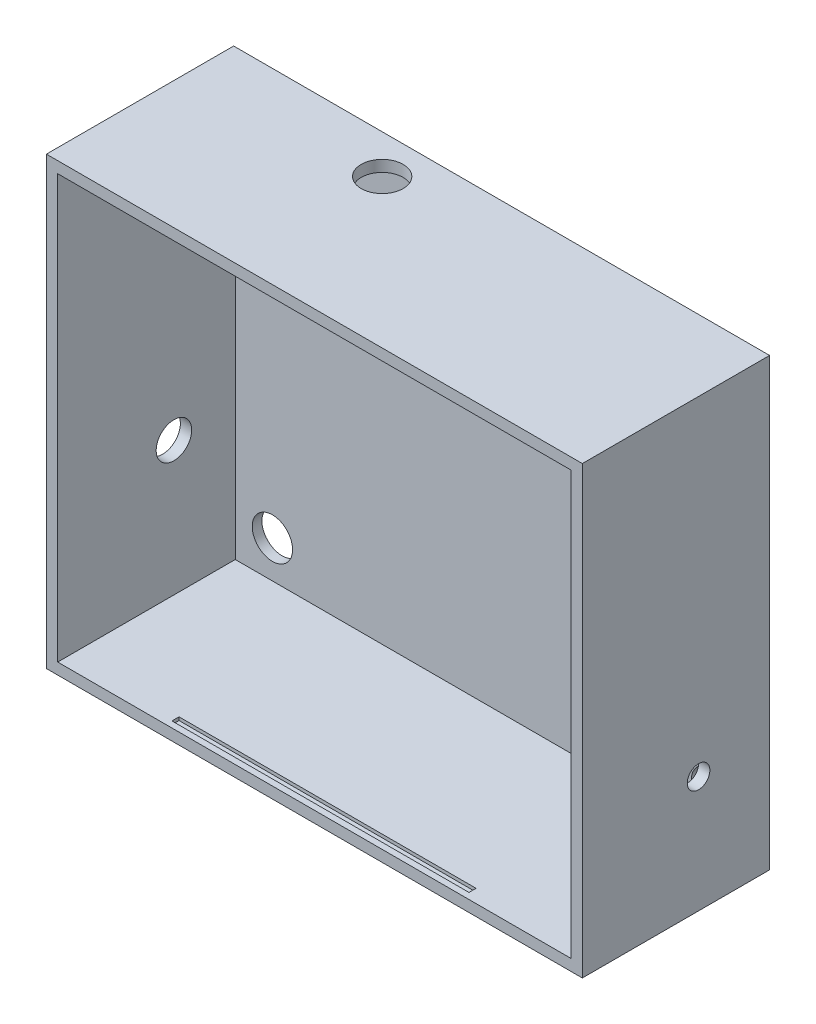
SolidWorks part; units mm, degrees
ref_plane "정면" through (0, 0, 0) normal (0, 0, 1) x (1, 0, 0)
ref_plane "윗면" through (0, 0, 0) normal (0, 1, 0) x (1, 0, 0)
ref_plane "우측면" through (0, 0, 0) normal (1, 0, 0) x (0, 0, -1)
sketch "스케치1" plane through (0, 0, 0) normal (0, 0, 1) x (1, 0, 0)
  line L1 (-83, -69) -> (83, -69)
  line L2 (-83, -69) -> (-83, 69)
  line L3 (-83, 69) -> (83, 69)
  line L4 (83, -69) -> (83, 69)
  line L5 (-83, -69) -> (83, 69) construction
  line L6 (-83, 69) -> (83, -69) construction
  point P0 (0, 0)
  dimension "D1" = 166
  dimension "D2" = 138
extrude "보스-돌출1" add sketch "스케치1" along normal blind 3
sketch "스케치2" plane through (0, 0, 3) normal (0, 0, 1) x (1, 0, 0)
  line L1 (-83, -69) -> (83, -69)
  line L2 (-83, -69) -> (-83, 69)
  line L3 (-83, 69) -> (83, 69)
  line L4 (83, -69) -> (83, 69)
  line L5 (-83, -69) -> (83, 69) construction
  line L6 (-83, 69) -> (83, -69) construction
  line L7 (-79.5, -65.5) -> (79.5, -65.5)
  line L8 (-79.5, -65.5) -> (-79.5, 65.5)
  line L9 (-79.5, 65.5) -> (79.5, 65.5)
  line L10 (79.5, -65.5) -> (79.5, 65.5)
  line L11 (-79.5, -65.5) -> (79.5, 65.5) construction
  line L12 (-79.5, 65.5) -> (79.5, -65.5) construction
  point P0 (0, 0)
  point P7 (0, 0)
  line M9 (83, -69) -> (83, 69)
  line M10 (83, 69) -> (-83, 69)
  line M11 (-83, 69) -> (-83, -69)
  line M12 (-83, -69) -> (83, -69)
  dimension "D1" = 159
  dimension "D2" = 131
extrude "보스-돌출2" add sketch "스케치2" along normal blind 55 contours L10 L7 L8 L9 M12 M9 M10 M11
sketch "스케치3" plane through (0, 0, 3) normal (0, 0, 1) x (1, 0, 0)
  line L0 (-83, 69) -> (-83, -69) construction
  line L1 (83, 69) -> (-83, 69) construction
  line L2 (0, 0) -> (-67.1963, 0) construction
  line L3 (0, 0) -> (0, -54.1905) construction
  circle A1 centre (-68, 54) radius 6.25
  circle A2 centre (-68, -54) radius 6.25
  circle A3 centre (68, -54) radius 6.25
  circle A4 centre (68, 54) radius 6.25
  dimension "D2" = 15
  dimension "D3" = 12.5
  dimension "D1" = 15
extrude "컷-돌출4" cut sketch "스케치3" against normal up to next
sketch "스케치4" plane through (0, 65.5, 0) normal (0, -1, 0) x (1, 0, 0)
  line L0 (-79.5, 58) -> (79.5, 58) construction
  line L1 (-46, 56.1) -> (46, 56.1)
  line L2 (-46, 56.1) -> (-46, 53.9)
  line L3 (-46, 53.9) -> (46, 53.9)
  line L4 (46, 56.1) -> (46, 53.9)
  line L5 (-46, 56.1) -> (46, 53.9) construction
  line L6 (-46, 53.9) -> (46, 56.1) construction
  point P0 (0, 55)
  dimension "D1" = 3
  dimension "D2" = 2.2
  dimension "D3" = 92
extrude "컷-돌출5" cut sketch "스케치4" against normal blind 1
sketch "스케치5" plane through (0, -65.5, 0) normal (0, 1, 0) x (1, 0, 0)
  line L0 (-79.5, -58) -> (79.5, -58) construction
  line L1 (-46.015, -53.9) -> (45.985, -53.9)
  line L2 (-46.015, -53.9) -> (-46.015, -56.1)
  line L3 (-46.015, -56.1) -> (45.985, -56.1)
  line L4 (45.985, -53.9) -> (45.985, -56.1)
  line L5 (-46.015, -53.9) -> (45.985, -56.1) construction
  line L6 (-46.015, -56.1) -> (45.985, -53.9) construction
  point P0 (-0.015, -55)
  point P7 (0, -58)
  dimension "D1" = 92
  dimension "D2" = 3
  dimension "D3" = 2.2
extrude "컷-돌출6" cut sketch "스케치5" against normal blind 1
sketch "스케치6" plane through (0, 69, 0) normal (0, 1, 0) x (1, 0, 0)
  line L0 (83, 0) -> (-83, 0) construction
  line L1 (-83, -58) -> (-83, 0) construction
  circle A0 centre (-25, -12) radius 6.5
  dimension "D1" = 12
  dimension "D2" = 58
extrude "컷-돌출7" cut sketch "스케치6" against normal blind 10
sketch "스케치7" plane through (-83, 0, 0) normal (-1, 0, 0) x (0, 0, 1)
  line L0 (58, -69) -> (0, -69) construction
  line L1 (0, 69) -> (0, -69) construction
  circle A0 centre (22, -24) radius 5.5
  dimension "D1" = 45
  dimension "D2" = 22
extrude "컷-돌출8" cut sketch "스케치7" against normal blind 10
sketch "스케치8" plane through (83, 0, 0) normal (1, 0, 0) x (0, 0, -1)
  line L0 (-58, -69) -> (0, -69) construction
  line L1 (0, -69) -> (0, 69) construction
  circle A0 centre (-22, -33) radius 3.5
  dimension "D1" = 36
  dimension "D2" = 22
extrude "컷-돌출9" cut sketch "스케치8" against normal blind 10
